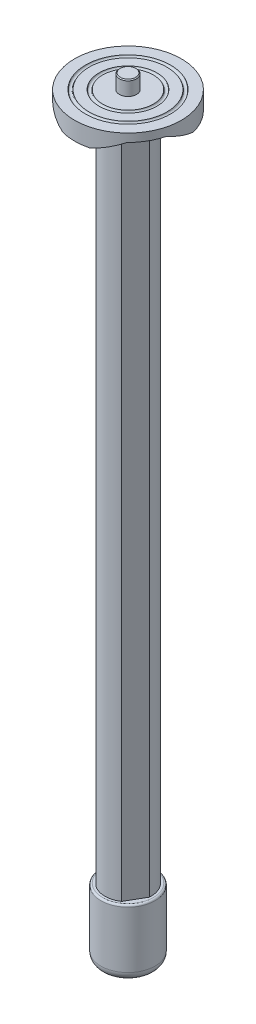
SolidWorks part; units mm, degrees
ref_plane "Front Plane" through (0, 0, 0) normal (0, 0, 1) x (1, 0, 0)
ref_plane "Top Plane" through (0, 0, 0) normal (0, 1, 0) x (1, 0, 0)
ref_plane "Right Plane" through (0, 0, 0) normal (1, 0, 0) x (0, 0, -1)
sketch "Sketch2" plane through (0, 0, 0) normal (0, 1, 0) x (1, 0, 0)
  line L0 (-5.6461, 11.6544) -> (5.6461, 11.6544) construction
  line L1 (12.916, -0.9375) -> (7.2699, -10.7168) construction
  line L2 (-5.6, 11.4544) -> (5.6, 11.4544)
  line L3 (12.7198, -0.8774) -> (7.1198, -10.5769)
  line L4 (-7.1198, -10.5769) -> (-12.7198, -0.8774)
  line L5 (-7.2699, -10.7168) -> (-12.916, -0.9375) construction
  arc A0 (-5.6, 11.4544) -> (-12.7198, -0.8774) centre (0, 0) ccw
  arc A1 (-7.1198, -10.5769) -> (7.1198, -10.5769) centre (0, 0) ccw
  arc A2 (12.7198, -0.8774) -> (5.6, 11.4544) centre (0, 0) ccw
  arc A3 (12.916, -0.9375) -> (5.6461, 11.6544) centre (0, 0) ccw construction
  arc A4 (-7.2699, -10.7168) -> (7.2699, -10.7168) centre (0, 0) ccw construction
  arc A5 (-5.6461, 11.6544) -> (-12.916, -0.9375) centre (0, 0) ccw construction
  dimension "D1" = 0.2
extrude "Extrude1" add sketch "Sketch2" along normal mid plane 370
sketch "Sketch3" plane through (0, 185, 0) normal (0, 1, 0) x (1, 0, 0)
  circle A0 centre (0, 0) radius 29.5
  dimension "D1" = 59
extrude "Extrude2" add sketch "Sketch3" along normal blind 10 separate body
ref_plane "Plane1" through (0, 0, -35) normal (0, 0, 1) x (1, 0, 0)
sketch "Sketch7" plane through (0, 0, 0) normal (0, 0, 1) x (1, 0, 0)
  line L0 (0, 203.8228) -> (0, 175.1069) construction
  line L1 (29.5, 195) -> (-29.5, 195) construction
  circle A0 centre (15, 195) radius 1
  circle A1 centre (22.5, 195) radius 1
  dimension "D1" = 30
  dimension "D2" = 45
  dimension "D3" = 2
revolve "Cut-Revolve1" cut sketch "Sketch7" angle 360 about L0
sketch "Sketch6" plane through (0, 185, 0) normal (0, -1, 0) x (1, 0, 0)
  circle A2 centre (0, 0) radius 25.5
  circle A3 centre (0, 0) radius 25.5
  circle A4 centre (0, 0) radius 29.5
  circle A5 centre (0, 0) radius 29.5
  dimension "D1" = 4
  dimension "D2" = 0
extrude "Extrude4" cut sketch "Sketch6" against normal blind 5.5 flip side to cut
sketch "Sketch4" plane through (0, 0, -35) normal (0, 0, 1) x (1, 0, 0)
  line L0 (0, 203.7466) -> (0, 160.4159) construction
  line L1 (8, 190.5) -> (-8, 190.5)
  line L2 (-8, 190.5) -> (-21, 185)
  line L3 (-29.5, 185) -> (29.5, 185) construction
  line L4 (29.5, 195) -> (-29.5, 195) construction
  line L5 (-21, 185) -> (21, 185)
  line L6 (8, 190.5) -> (21, 185)
  point P12 (0, 185)
  point P13 (0, 190.5)
  dimension "D1" = 16
  dimension "D2" = 4.5
  dimension "D3" = 42
  dimension "D4" = 5.5
extrude "Extrude3" cut sketch "Sketch4" along normal blind 23
pattern_circular "CirPattern1" count 3 over 360 about axis through (0, 0, 0) along (0, 1, 0) of "Extrude3"
sketch "Sketch8" plane through (0, 195, 0) normal (0, 1, 0) x (1, 0, 0)
  circle A0 centre (0, 0) radius 4.7625
  dimension "D1" = 9.525
extrude "Extrude5" add sketch "Sketch8" along normal blind 8 separate body
chamfer "Chamfer1" distance 0.5 angle 45 1 edges at (0, 203, 4.7625)
sketch "Sketch9" plane through (0, 185, 0) normal (0, 1, 0) x (1, 0, 0)
  line L3 (-12.7198, -0.8774) -> (-7.1198, -10.5769)
  line L4 (7.1198, -10.5769) -> (12.7198, -0.8774)
  line L5 (5.6, 11.4544) -> (-5.6, 11.4544)
  line L6 (-12.7198, -0.8774) -> (-7.1198, -10.5769)
  line L7 (7.1198, -10.5769) -> (12.7198, -0.8774)
  line L8 (5.6, 11.4544) -> (-5.6, 11.4544)
  arc A3 (-5.6, 11.4544) -> (-12.7198, -0.8774) centre (0, 0) ccw
  arc A4 (-7.1198, -10.5769) -> (7.1198, -10.5769) centre (0, 0) ccw
  arc A5 (12.7198, -0.8774) -> (5.6, 11.4544) centre (0, 0) ccw
  arc A6 (-5.6, 11.4544) -> (-12.7198, -0.8774) centre (0, 0) ccw
  arc A7 (-7.1198, -10.5769) -> (7.1198, -10.5769) centre (0, 0) ccw
  arc A8 (12.7198, -0.8774) -> (5.6, 11.4544) centre (0, 0) ccw
  dimension "D1" = 0
extrude "Extrude6" add sketch "Sketch9" along normal blind 8 separate body
sketch "Sketch10" plane through (0, 0, 0) normal (0, 0, 1) x (1, 0, 0)
  line L0 (0, -169.776) -> (0, -233.5826) construction
  line L1 (15, -185) -> (15, -220)
  line L2 (-7.1198, -185) -> (7.1198, -185) construction
  line L3 (0, -185) -> (15, -185)
  line L4 (-8.9046, -225) -> (11.9553, -225) construction
  line L5 (0, -185) -> (0, -225)
  arc A0 (0, -225) -> (15, -220) centre (0, -200) ccw
  dimension "D1" = 35
  dimension "D2" = 30
  dimension "D3" = 40
revolve "Revolve1" add sketch "Sketch10" angle 360 about L5
fillet "Fillet1" radius 5 1 edges at (-15, -220, 0)
fillet "Fillet2" radius 1 1 edges at (-15, -185, 0)
combine bodies "Combine1" operation type add bodies to combine 111 101
